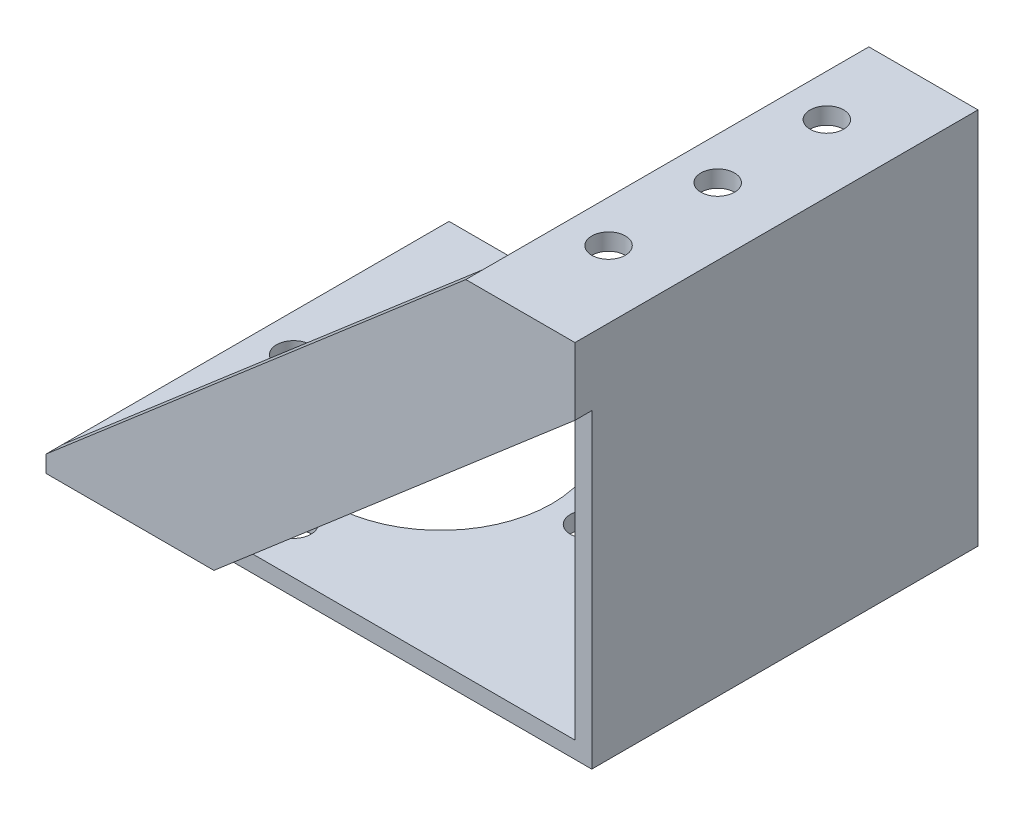
SolidWorks part; units mm, degrees
material "AISI 304"
ref_plane "前视基准面" through (0, 0, 0) normal (0, 0, 1) x (1, 0, 0)
ref_plane "上视基准面" through (0, 0, 0) normal (0, 1, 0) x (1, 0, 0)
ref_plane "右视基准面" through (0, 0, 0) normal (1, 0, 0) x (0, 0, -1)
sketch "Sketch1" plane through (0, 0, 0) normal (0, 0, 1) x (1, 0, 0)
  line L0 (0, 0) -> (0, 45)
  line L1 (0, 45) -> (-13, 45)
  line L2 (-13, 45) -> (-13, 43)
  line L3 (-13, 43) -> (-2, 43)
  line L4 (-2, 43) -> (-2, 2)
  line L5 (-2, 2) -> (-63, 2)
  line L6 (-63, 2) -> (-63, 0)
  line L7 (-63, 0) -> (0, 0)
  point P9 (-13, 44)
  dimension "D1" = 41
  dimension "D2" = 2
  dimension "D3" = 2
  dimension "D4" = 2
  dimension "D5" = 11
  dimension "D6" = 50
extrude "Boss-Extrude1" add sketch "Sketch1" along normal blind 46
sketch "Sketch2" plane through (0, 0, 0) normal (0, -1, 0) x (1, 0, 0)
  line L0 (-63, 23) -> (0, 23) construction
  line L1 (-63, 46) -> (-63, 0) construction
  line L2 (0, 46) -> (0, 0) construction
  line L3 (-41, 0) -> (-41, 46) construction
  line L4 (-63, 0) -> (0, 0) construction
  line L5 (-63, 46) -> (0, 46) construction
  circle A0 centre (-41, 23) radius 13.25
  circle A1 centre (-41, 23) radius 17.5 construction
  circle A2 centre (-41, 40.5) radius 2.05
  circle A3 centre (-58.5, 23) radius 2.05
  circle A4 centre (-23.5, 23) radius 2.05
  circle A5 centre (-41, 5.5) radius 2.05
  dimension "D2" = 4.1
  dimension "D3" = 4.1
  dimension "D4" = 4.1
  dimension "D5" = 4.1
  dimension "D6" = 35
  dimension "D7" = 26.5
  dimension "D1" = 22
extrude "Cut-Extrude1" cut sketch "Sketch2" against normal blind 2
sketch "Sketch3" plane through (0, 45, 0) normal (0, 1, 0) x (1, 0, 0)
  line L0 (-8, 0) -> (-8, -46) construction
  line L1 (0, 0) -> (-13, 0) construction
  line L2 (0, -46) -> (-13, -46) construction
  line L3 (-13, -46) -> (-13, 0) construction
  circle A0 centre (-8, -10) radius 2
  circle A1 centre (-8, -23) radius 2
  circle A2 centre (-8, -36) radius 2
  dimension "D2" = 4
  dimension "D3" = 4
  dimension "D4" = 4
  dimension "D6" = 10
  dimension "D7" = 13
  dimension "D1" = 5
  dimension "D5" = 10
extrude "Cut-Extrude2" cut sketch "Sketch3" against normal blind 100
sketch "Sketch4" plane through (0, 0, 46) normal (0, 0, 1) x (1, 0, 0)
  line L0 (-63, 2) -> (-13, 45)
  line L6 (-63, 0) -> (-63, 2)
  line L11 (-13, 45) -> (0, 45)
  line L12 (0, 45) -> (0, 36.98)
  line L13 (0, 0) -> (0, 45) construction
  line L14 (0, 36.98) -> (-43, 0)
  line L15 (-63, 0) -> (0, 0) construction
  line L16 (-43, 0) -> (-63, 0)
  dimension "D1" = 20
extrude "Boss-Extrude2" add sketch "Sketch4" along normal blind 2
